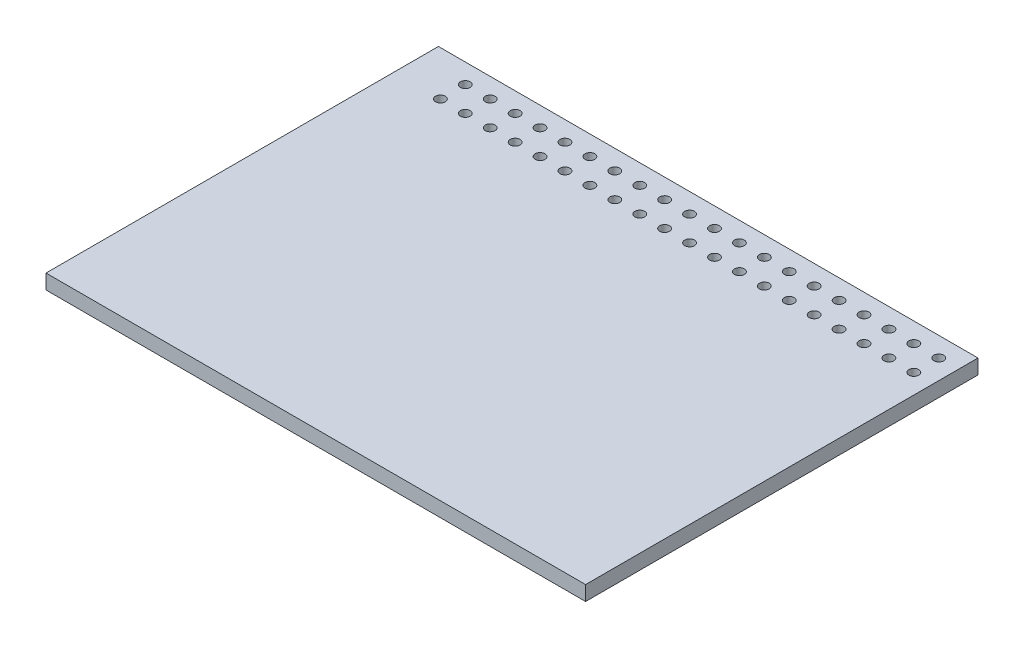
SolidWorks part; units mm, degrees
ref_plane "Front Plane" through (0, 0, 0) normal (0, 0, 1) x (1, 0, 0)
ref_plane "Top Plane" through (0, 0, 0) normal (0, 1, 0) x (1, 0, 0)
ref_plane "Right Plane" through (0, 0, 0) normal (1, 0, 0) x (0, 0, -1)
sketch "Sketch1" plane through (0, 0, 0) normal (0, 1, 0) x (1, 0, 0)
  line L1 (-27.5, -20) -> (27.5, -20)
  line L2 (-27.5, -20) -> (-27.5, 20)
  line L3 (-27.5, 20) -> (27.5, 20)
  line L4 (27.5, -20) -> (27.5, 20)
  line L5 (-27.5, -20) -> (27.5, 20) construction
  line L6 (-27.5, 20) -> (27.5, -20) construction
  circle A0 centre (25.5, 18) radius 0.5
  circle A1 centre (22.96, 18) radius 0.5
  circle A2 centre (20.42, 18) radius 0.5
  circle A3 centre (17.88, 18) radius 0.5
  circle A4 centre (15.34, 18) radius 0.5
  circle A5 centre (12.8, 18) radius 0.5
  circle A6 centre (10.26, 18) radius 0.5
  circle A7 centre (7.72, 18) radius 0.5
  circle A8 centre (5.18, 18) radius 0.5
  circle A9 centre (2.64, 18) radius 0.5
  circle A10 centre (0.1, 18) radius 0.5
  circle A11 centre (-2.44, 18) radius 0.5
  circle A12 centre (-4.98, 18) radius 0.5
  circle A13 centre (-7.52, 18) radius 0.5
  circle A14 centre (-10.06, 18) radius 0.5
  circle A15 centre (-12.6, 18) radius 0.5
  circle A16 centre (-15.14, 18) radius 0.5
  circle A17 centre (-17.68, 18) radius 0.5
  circle A18 centre (-20.22, 18) radius 0.5
  circle A19 centre (-22.76, 18) radius 0.5
  circle A20 centre (22.96, 15.46) radius 0.5
  circle A21 centre (20.42, 15.46) radius 0.5
  circle A22 centre (17.88, 15.46) radius 0.5
  circle A23 centre (15.34, 15.46) radius 0.5
  circle A24 centre (12.8, 15.46) radius 0.5
  circle A25 centre (10.26, 15.46) radius 0.5
  circle A26 centre (7.72, 15.46) radius 0.5
  circle A27 centre (5.18, 15.46) radius 0.5
  circle A28 centre (2.64, 15.46) radius 0.5
  circle A29 centre (0.1, 15.46) radius 0.5
  circle A30 centre (-2.44, 15.46) radius 0.5
  circle A31 centre (-4.98, 15.46) radius 0.5
  circle A32 centre (-7.52, 15.46) radius 0.5
  circle A33 centre (-10.06, 15.46) radius 0.5
  circle A34 centre (-12.6, 15.46) radius 0.5
  circle A35 centre (-15.14, 15.46) radius 0.5
  circle A36 centre (-17.68, 15.46) radius 0.5
  circle A37 centre (-20.22, 15.46) radius 0.5
  circle A38 centre (-22.76, 15.46) radius 0.5
  circle A39 centre (25.5, 15.46) radius 0.5
  point P0 (0, 0)
  point P8 (0, 0)
  point P9 (-15.436, 28)
  point P10 (35.6169, 25.5171)
  point P89 (32.92, 25.46)
  point P90 (0, 0)
  dimension "D3" = 1
  dimension "D1" = 40
  dimension "D2" = 55
  dimension "D4" = 2
  dimension "D5" = 2
  dimension "D8" = 2.54
  dimension "D9" = 2.54
  dimension "D6" = 20
  dimension "D7" = 2
extrude "Boss-Extrude1" add sketch "Sketch1" along normal blind 1.5
